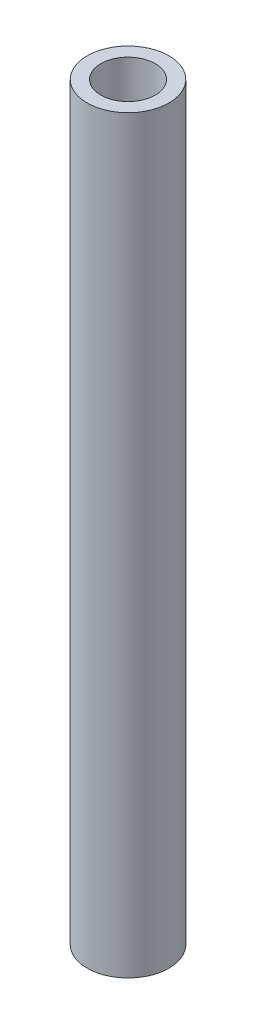
SolidWorks part; units mm, degrees
material "acero"
ref_plane "Alzado" through (0, 0, 0) normal (0, 0, 1) x (1, 0, 0)
ref_plane "Planta" through (0, 0, 0) normal (0, 1, 0) x (1, 0, 0)
ref_plane "Vista lateral" through (0, 0, 0) normal (1, 0, 0) x (0, 0, -1)
sketch "Croquis1" plane through (0, 0, 0) normal (0, 0, 1) x (1, 0, 0)
  line L0 (0, -0.7202) -> (0, 0.7202)
  line L2 (3, -27.5) -> (-3, -27.5)
  line L3 (3, -27.5) -> (3, 27.5)
  line L4 (3, 27.5) -> (-3, 27.5)
  line L5 (-3, -27.5) -> (-3, 27.5)
  line L6 (3, -27.5) -> (-3, 27.5) construction
  line L7 (3, 27.5) -> (-3, -27.5) construction
  line L8 (2, -27.5) -> (-2, -27.5)
  line L9 (2, -27.5) -> (2, 27.5)
  line L10 (2, 27.5) -> (-2, 27.5)
  line L11 (-2, -27.5) -> (-2, 27.5)
  line L12 (2, -27.5) -> (-2, 27.5) construction
  line L13 (2, 27.5) -> (-2, -27.5) construction
  point P1 (0, 0)
  point P3 (0, 0)
  dimension "D1" = 6
  dimension "D2" = 4
  dimension "D3" = 55
revolve "Revolución1" add sketch "Croquis1" angle 360 about L0
